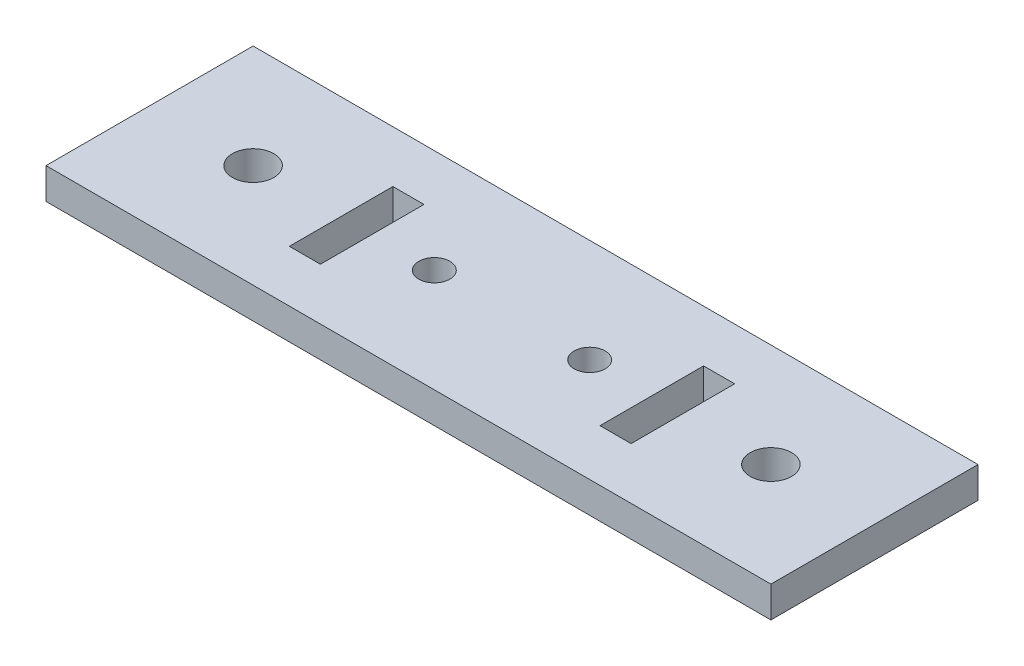
SolidWorks part; units mm, degrees
ref_plane "Front Plane" through (0, 0, 0) normal (0, 0, 1) x (1, 0, 0)
ref_plane "Top Plane" through (0, 0, 0) normal (0, 1, 0) x (1, 0, 0)
ref_plane "Right Plane" through (0, 0, 0) normal (1, 0, 0) x (0, 0, -1)
sketch "Sketch1" plane through (0, 0, 0) normal (0, 1, 0) x (1, 0, 0)
  line L0 (20, 20) -> (20, 0) construction
  line L1 (0, 0) -> (70, 0)
  line L2 (0, 0) -> (0, 20)
  line L3 (0, 20) -> (70, 20)
  line L4 (70, 0) -> (70, 20)
  line L5 (50, 20) -> (50, 0) construction
  line L6 (35, 20) -> (35, 0) construction
  line L7 (18.5, 15) -> (21.5, 15)
  line L8 (18.5, 15) -> (18.5, 5)
  line L9 (18.5, 5) -> (21.5, 5)
  line L10 (21.5, 15) -> (21.5, 5)
  line L11 (51.5, 5) -> (48.5, 5)
  line L12 (48.5, 15) -> (48.5, 5)
  line L13 (51.5, 15) -> (51.5, 5)
  line L14 (51.5, 15) -> (48.5, 15)
  line L15 (10, 20) -> (10, 0) construction
  line L16 (0, 10) -> (20, 10) construction
  line L17 (27.5, 0) -> (27.5, 20) construction
  circle A0 centre (10, 10) radius 2
  circle A1 centre (27.5, 10) radius 1.5
  circle A2 centre (60, 10) radius 2
  circle A3 centre (42.5, 10) radius 1.5
  dimension "D10" = 7.5
  dimension "D1" = 70
  dimension "D2" = 20
  dimension "D3" = 20
  dimension "D4" = 20
  dimension "D5" = 3
  dimension "D6" = 10
  dimension "D7" = 1.5
  dimension "D8" = 5
  dimension "D9" = 10
extrude "Boss-Extrude1" add sketch "Sketch1" along normal blind 3
